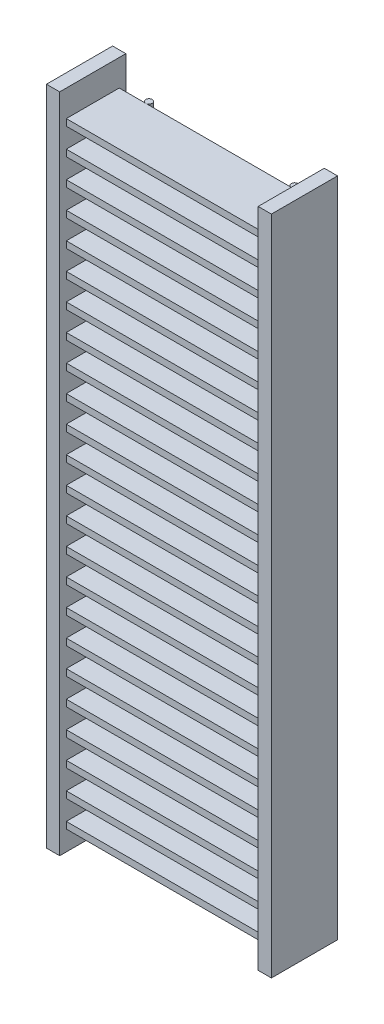
SolidWorks part; units mm, degrees
ref_plane "Front Plane" through (0, 0, 0) normal (0, 0, 1) x (1, 0, 0)
ref_plane "Top Plane" through (0, 0, 0) normal (0, 1, 0) x (1, 0, 0)
ref_plane "Right Plane" through (0, 0, 0) normal (1, 0, 0) x (0, 0, -1)
sketch "Sketch1" plane through (0, 0, 0) normal (0, 0, 1) x (1, 0, 0)
  line L1 (-85, 130.3846) -> (-75, 130.3846)
  line L2 (-85, 130.3846) -> (-85, -369.6154)
  line L3 (-85, -369.6154) -> (-75, -369.6154)
  line L4 (-75, 130.3846) -> (-75, -369.6154)
  line L5 (-85, 130.3846) -> (-75, -369.6154) construction
  line L6 (-85, -369.6154) -> (-75, 130.3846) construction
  line L7 (75, 130.3846) -> (85, 130.3846)
  line L8 (75, 130.3846) -> (75, -369.6154)
  line L9 (75, -369.6154) -> (85, -369.6154)
  line L10 (85, 130.3846) -> (85, -369.6154)
  line L11 (75, 130.3846) -> (85, -369.6154) construction
  line L12 (75, -369.6154) -> (85, 130.3846) construction
  point P4 (-80, -119.6154)
  point P9 (80, -119.6154)
  dimension "D1" = 10
  dimension "D2" = 10
  dimension "D3" = 150
  dimension "D4" = 500
  dimension "D5" = 500
  dimension "D6" = 75
extrude "Boss-Extrude1" add sketch "Sketch1" along normal blind 50
sketch "Sketch2" plane through (-75, 0, 0) normal (1, 0, 0) x (0, 0, -1)
  line L0 (0, -369.6154) -> (0, 130.3846) construction
  line L1 (-45, 110.3846) -> (-5, 110.3846)
  line L2 (-45, 110.3846) -> (-45, 105.3846)
  line L3 (-45, 105.3846) -> (-5, 105.3846)
  line L4 (-5, 110.3846) -> (-5, 105.3846)
  line L5 (-45, 110.3846) -> (-5, 105.3846) construction
  line L6 (-45, 105.3846) -> (-5, 110.3846) construction
  line L7 (-50, 130.3846) -> (0, 130.3846) construction
  point P4 (-25, 107.8846)
  dimension "D1" = 5
  dimension "D2" = 40
  dimension "D3" = 5
  dimension "D4" = 20
extrude "Boss-Extrude2" add sketch "Sketch2" along normal up to next (160 mm away)
pattern_linear "LPattern1" count 24 spacing 20 along (0, -1, 0) of "Boss-Extrude2"
sketch "Sketch4" plane through (0, 110.3846, 0) normal (0, 1, 0) x (1, 0, 0)
  line L0 (75, -5) -> (-75, -5) construction
  circle A0 centre (-55, -2.5) radius 2.5
  circle A1 centre (55, -2.5) radius 2.5
  dimension "D1" = 5
  dimension "D2" = 5
  dimension "D3" = 55
  dimension "D4" = 55
extrude "Boss-Extrude3" add sketch "Sketch4" against normal up to surface (465 mm away) separate body up to face at (0, -354.6154, 25)
